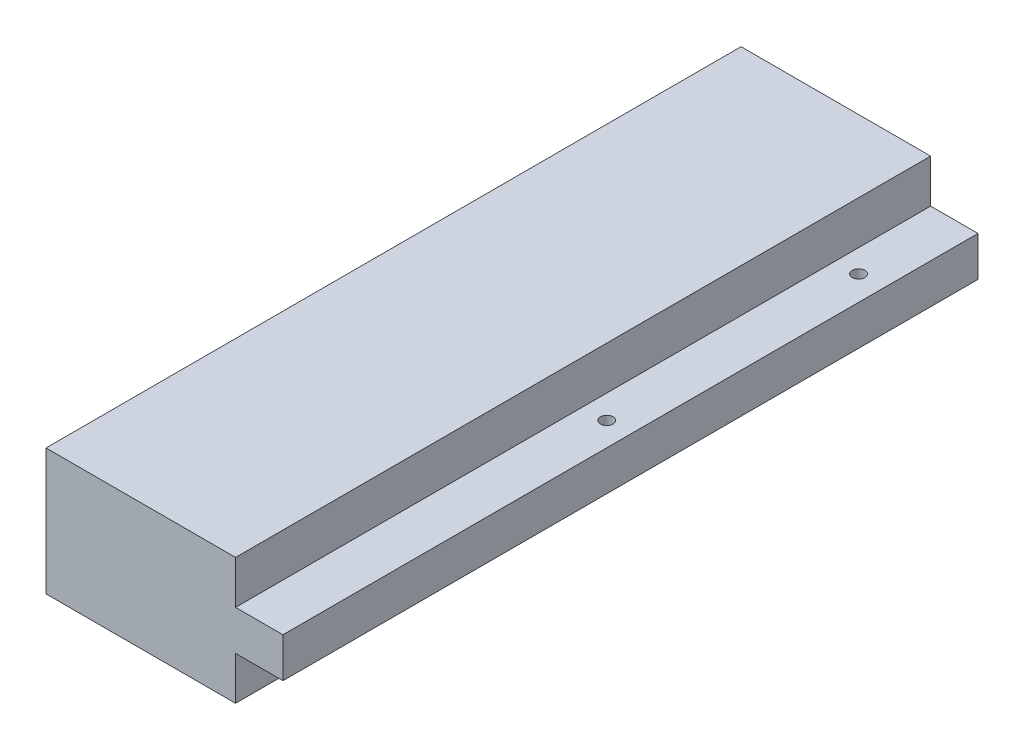
SolidWorks part; units mm, degrees
ref_plane "Plan de face" through (0, 0, 0) normal (0, 0, 1) x (1, 0, 0)
ref_plane "Plan de dessus" through (0, 0, 0) normal (0, 1, 0) x (1, 0, 0)
ref_plane "Plan de droite" through (0, 0, 0) normal (1, 0, 0) x (0, 0, -1)
sketch "Esquisse1" plane through (0, 0, 0) normal (0, 0, 1) x (1, 0, 0)
  line L0 (0, 0) -> (300, 0)
  line L1 (300, 0) -> (300, 68.5)
  line L2 (300, 68.5) -> (375, 68.5)
  line L3 (375, 68.5) -> (375, 131.5)
  line L4 (375, 131.5) -> (300, 131.5)
  line L5 (300, 131.5) -> (300, 200)
  line L6 (300, 200) -> (0, 200)
  line L7 (0, 200) -> (0, 0)
  dimension "D1" = 300
  dimension "D2" = 200
  dimension "D3" = 75
  dimension "D4" = 63
  dimension "D5" = 68.5
extrude "Boss.-Extru.1" add sketch "Esquisse1" along normal blind 1100
sketch "Esquisse2" plane through (0, 68.5, 0) normal (0, -1, 0) x (1, 0, 0)
  line L0 (337.5, 0) -> (337.5, 1100) construction
  line L1 (300, 0) -> (375, 0) construction
  line L2 (300, 1100) -> (375, 1100) construction
  circle A0 centre (337.5, 550) radius 10
extrude "Enlèv. mat.-Extru.1" cut sketch "Esquisse2" against normal up to next
sketch "Esquisse3" plane through (0, 68.5, 0) normal (0, -1, 0) x (1, 0, 0)
  circle A0 centre (336.0114, 150) radius 10
  circle A1 centre (337.5, 550) radius 10 construction
  dimension "D1" = 400
extrude "Enlèv. mat.-Extru.2" cut sketch "Esquisse3" against normal up to next
